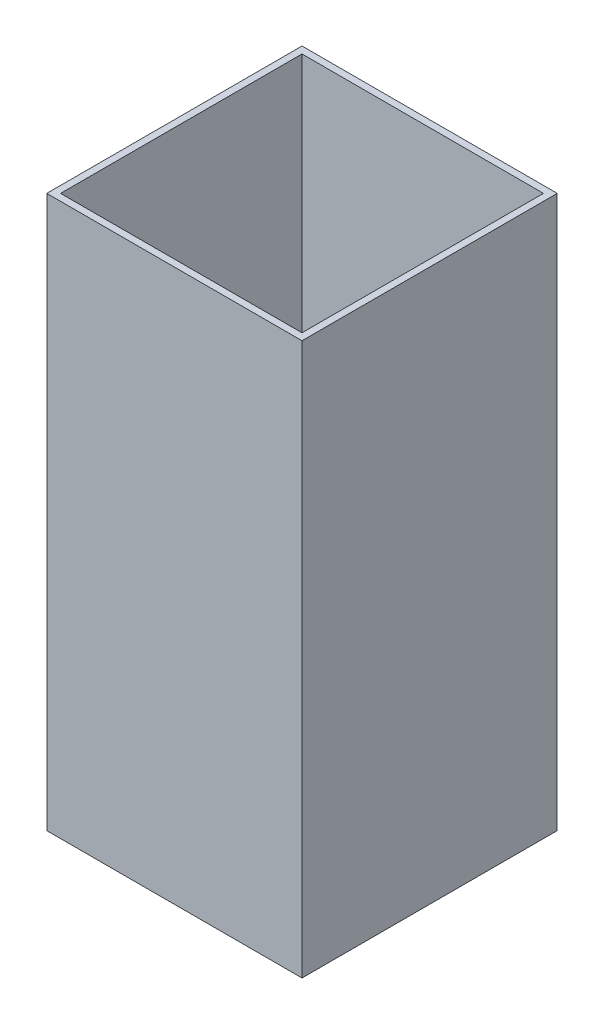
SolidWorks part; units mm, degrees
ref_plane "Front Plane" through (0, 0, 0) normal (0, 0, 1) x (1, 0, 0)
ref_plane "Top Plane" through (0, 0, 0) normal (0, 1, 0) x (1, 0, 0)
ref_plane "Right Plane" through (0, 0, 0) normal (1, 0, 0) x (0, 0, -1)
sketch "Sketch1" plane through (0, 0, 0) normal (0, 1, 0) x (1, 0, 0)
  line L0 (-185, -185) -> (185, -185)
  line L1 (-175, 175) -> (175, 175)
  line L2 (-175, 175) -> (-175, -175)
  line L3 (-175, -175) -> (175, -175)
  line L4 (175, 175) -> (175, -175)
  line L5 (-175, 175) -> (175, -175) construction
  line L6 (-175, -175) -> (175, 175) construction
  line L7 (185, 185) -> (185, -185)
  line L8 (-185, 185) -> (185, 185)
  line L9 (-185, 185) -> (-185, -185)
  point P0 (0, 0)
  dimension "D1" = 10
extrude "Boss-Extrude1" add sketch "Sketch1" along normal blind 800
